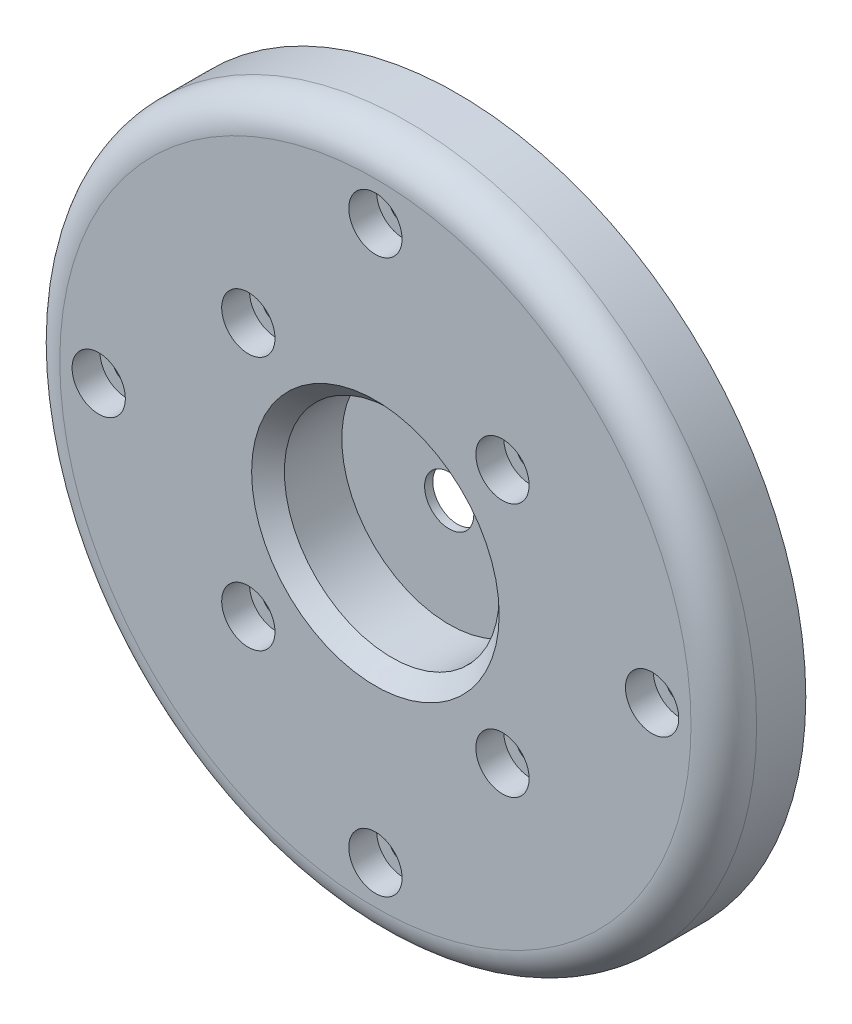
SolidWorks part; units mm, degrees
ref_plane "Ebene vorne" through (0, 0, 0) normal (0, 0, 1) x (1, 0, 0)
ref_plane "Ebene oben" through (0, 0, 0) normal (0, 1, 0) x (1, 0, 0)
ref_plane "Ebene rechts" through (0, 0, 0) normal (1, 0, 0) x (0, 0, -1)
sketch "Skizze3" plane through (0, 0, 0) normal (0, 0, 1) x (1, 0, 0)
  circle A0 centre (0, 0) radius 42.5
  dimension "D1" = 85
extrude "Aufsatz-Linear austragen1" add sketch "Skizze3" along normal blind 10
sketch "Skizze4" plane through (0, 0, 10) normal (0, 0, 1) x (1, 0, 0)
  circle A1 centre (0, 0) radius 3
  dimension "D1" = 6
extrude "Schnitt-Linear austragen1" cut sketch "Skizze4" against normal up to surface (10 mm away) up to face at (42.5, 0, 0)
sketch "Skizze5" plane through (0, 0, 10) normal (0, 0, 1) x (1, 0, 0)
  line L0 (0, 0) -> (-33.75, 0) construction
  line L1 (-15.5, -15.5) -> (15.5, -15.5) construction
  line L2 (-15.5, -15.5) -> (-15.5, 15.5) construction
  line L3 (-15.5, 15.5) -> (15.5, 15.5) construction
  line L4 (15.5, -15.5) -> (15.5, 15.5) construction
  line L5 (-15.5, -15.5) -> (15.5, 15.5) construction
  line L6 (-15.5, 15.5) -> (15.5, -15.5) construction
  circle A0 centre (-15.5, 15.5) radius 3.25
  circle A1 centre (-33.75, 0) radius 3.25
  point P0 (0, 0)
  point P10 (-26.1417, 0)
  dimension "D3" = 6.5
  dimension "D1" = 31
  dimension "D2" = 31
  dimension "D4" = 33.75
extrude "Schnitt-Linear austragen3" cut sketch "Skizze5" against normal blind 3.4
sketch "Skizze6" plane through (0, 0, 6.6) normal (0, 0, 1) x (1, 0, 0)
  circle A0 centre (-15.5, 15.5) radius 1.7
  circle A1 centre (-33.75, 0) radius 1.7
  dimension "D1" = 3.4
extrude "Schnitt-Linear austragen4" cut sketch "Skizze6" against normal up to surface (6.6 mm away) up to face at (3, 0, 0)
pattern_circular "Kreismuster1" count 4 over 360 about axis through (0, 0, 0) along (0, 0, 1) of "Schnitt-Linear austragen3", "Schnitt-Linear austragen4"
sketch "Skizze7" plane through (0, 0, 10) normal (0, 0, 1) x (1, 0, 0)
  circle A0 centre (0, 0) radius 13.1
  dimension "D1" = 26.2
extrude "Schnitt-Linear austragen5" cut sketch "Skizze7" against normal blind 9
fillet "Verrundung1" radius 4 1 edges at (42.5, 0, 10)
chamfer "Fase1" distance 2 angle 45 1 edges at (13.1, 0, 10)
